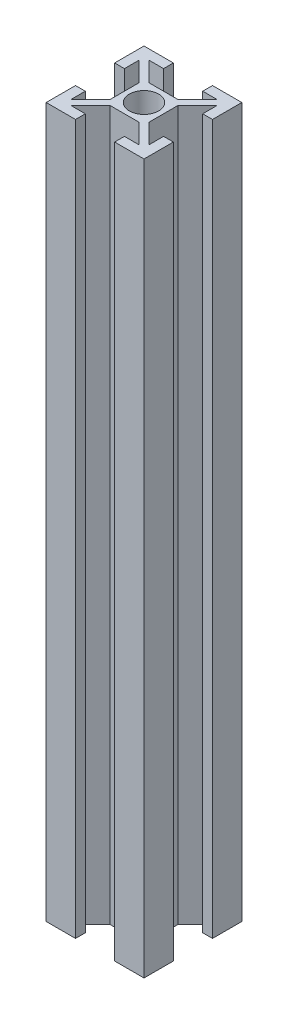
SolidWorks part; units mm, degrees
material "1060 Alloy"
ref_plane "Front Plane" through (0, 0, 0) normal (0, 0, 1) x (1, 0, 0)
ref_plane "Top Plane" through (0, 0, 0) normal (0, 1, 0) x (1, 0, 0)
ref_plane "Right Plane" through (0, 0, 0) normal (1, 0, 0) x (0, 0, -1)
sketch "2020 sketch" plane through (0, 0, 0) normal (0, 1, 0) x (1, 0, 0)
  line L0 (-4, 10) -> (-4, 8)
  line L1 (-10, 10) -> (-4, 10)
  line L2 (-10, 10) -> (-10, 4)
  line L3 (-10, -10) -> (-4, -10)
  line L4 (10, 10) -> (10, 4)
  line L5 (-10, 10) -> (10, -10) construction
  line L6 (-10, -10) -> (10, 10) construction
  line L7 (-4, 8) -> (-7, 8)
  line L8 (-7, 8) -> (-3, 4)
  line L9 (-3, 4) -> (3, 4)
  line L10 (3, 4) -> (7, 8)
  line L11 (7, 8) -> (4, 8)
  line L12 (4, 8) -> (4, 10)
  line L13 (4, 3) -> (4, -3)
  line L14 (8, 7) -> (4, 3)
  line L15 (8, 4) -> (8, 7)
  line L16 (10, 4) -> (8, 4)
  line L17 (8, -4) -> (10, -4)
  line L18 (8, -7) -> (8, -4)
  line L19 (4, -3) -> (8, -7)
  line L20 (3, -4) -> (-3, -4)
  line L21 (7, -8) -> (3, -4)
  line L22 (4, -8) -> (7, -8)
  line L23 (4, -10) -> (4, -8)
  line L24 (-4, -8) -> (-4, -10)
  line L25 (-7, -8) -> (-4, -8)
  line L26 (-3, -4) -> (-7, -8)
  line L27 (-4, -3) -> (-4, 3)
  line L28 (-8, -7) -> (-4, -3)
  line L29 (-8, -4) -> (-8, -7)
  line L30 (-10, -4) -> (-8, -4)
  line L31 (-8, 4) -> (-10, 4)
  line L32 (-8, 7) -> (-8, 4)
  line L33 (-4, 3) -> (-8, 7)
  line L34 (-10, -4) -> (-10, -10)
  line L35 (10, -4) -> (10, -10)
  line L36 (4, 10) -> (10, 10)
  line L37 (4, -10) -> (10, -10)
  circle A0 centre (0, 0) radius 3
  point P0 (0, 0)
  point P14 (4, 9)
  point P42 (0, 0)
  dimension "D9" = 6
  dimension "D1" = 20
  dimension "D2" = 20
  dimension "D3" = 8
  dimension "D4" = 6
  dimension "D5" = 6
  dimension "D6" = 2
  dimension "D7" = 4
  dimension "D8" = 4
extrude "Boss-Extrude1" add sketch "2020 sketch" along normal blind 145 contours A0 | L28 L27 L33 L32 L31 L2 L1 L0 L7 L8 L9 L10 L11 L12 L36 L4 L16 L15 L14 L13 L19 L18 L17 L35 L37 L23 L22 L21 L20 L26 L25 L24 L3 L34 L30 L29
